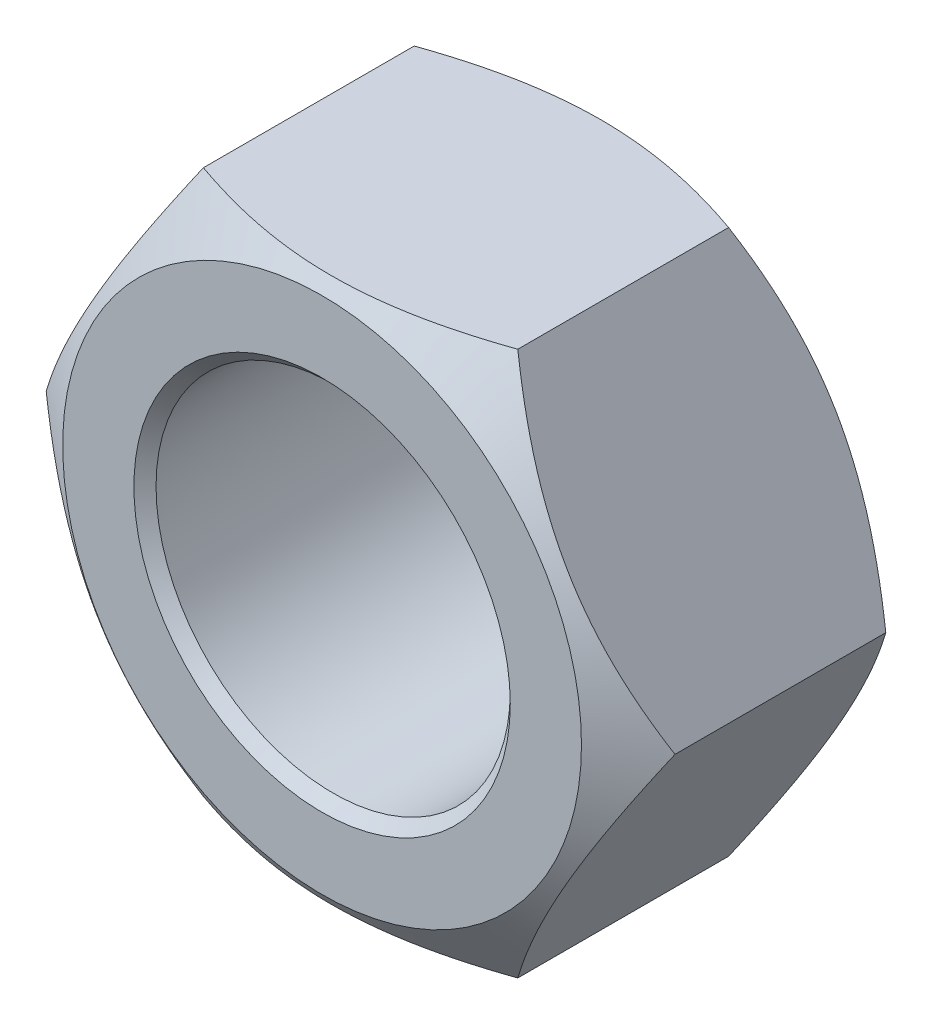
SolidWorks part; units mm, degrees
material "Plain Carbon Steel"
ref_plane "Спереди" through (0, 0, 0) normal (0, 0, 1) x (1, 0, 0)
ref_plane "Сверху" through (0, 0, 0) normal (0, 1, 0) x (1, 0, 0)
ref_plane "Справа" through (0, 0, 0) normal (1, 0, 0) x (0, 0, -1)
sketch "Sketch1" plane through (0, 0, 0) normal (0, 0, 1) x (1, 0, 0)
  line L1 (7.1, 0) -> (3.55, 6.1488)
  line L2 (3.55, 6.1488) -> (-3.55, 6.1488)
  line L3 (-3.55, 6.1488) -> (-7.1, 0)
  line L4 (-7.1, 0) -> (-3.55, -6.1488)
  line L5 (-3.55, -6.1488) -> (3.55, -6.1488)
  line L6 (3.55, -6.1488) -> (7.1, 0)
  circle A0 centre (0, 0) radius 6.1488 construction
  circle A1 centre (0, 0) radius 4
  dimension "D1" = 8
  dimension "D2" = 14.2
extrude "Boss-Extrude1" add sketch "Sketch1" along normal blind 6.5
chamfer "Chamfer1" distance 0.25 angle 45 2 edges at (4, 0, 0) (4, 0, 6.5)
sketch "Sketch3" plane through (0, 0, 0) normal (0, 1, 0) x (1, 0, 0)
  line L0 (0, -7.5) -> (0, 1) construction
  line L1 (-1, -7.5) -> (-4.4296, -7.5)
  line L2 (-4.4296, -7.5) -> (-8, -5)
  line L3 (-8, -5) -> (-8, -1.5)
  line L4 (-8, -1.5) -> (-4.4296, 1)
  line L5 (-4.4296, 1) -> (-1, 1)
  line L6 (-4.25, -6.5) -> (4.25, -6.5) construction
  line L7 (-1, 1.9255) -> (-9.5408, 1.9255)
  line L8 (-9.5408, 1.9255) -> (-9.5408, -8.9006)
  line L9 (-9.5408, -8.9006) -> (-1, -8.9006)
  line L10 (4.25, 0) -> (-4.25, 0) construction
  line L11 (-1, -8.9006) -> (-1, -7.5)
  line L12 (-1, 1) -> (-1, 1.9255)
  dimension "D1" = 1
  dimension "D2" = 1
  dimension "D3" = 35
  dimension "D4" = 35
  dimension "D5" = 1
  dimension "D6" = 7
  dimension "D7" = 3.5
revolve "Cut-Revolve1" cut sketch "Sketch3" angle 360 about L0
